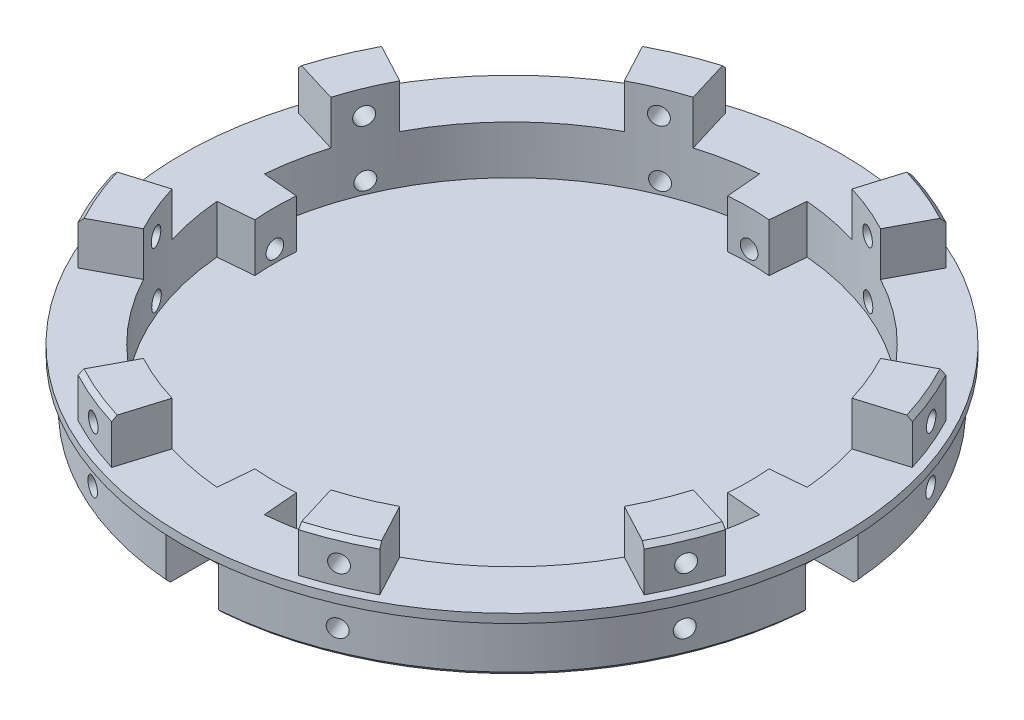
SolidWorks part; units mm, degrees
material "7075-T6, Piastra (SS)"
ref_plane "Piano frontale" through (0, 0, 0) normal (0, 0, 1) x (1, 0, 0)
ref_plane "Piano superiore" through (0, 0, 0) normal (0, 1, 0) x (1, 0, 0)
ref_plane "Piano destro" through (0, 0, 0) normal (1, 0, 0) x (0, 0, -1)
sketch "Schizzo1" plane through (0, 0, 0) normal (0, 0, 1) x (1, 0, 0)
  line L1 (-73, 24) -> (-62, 24)
  line L4 (0, 3) -> (0, 0)
  line L5 (0, 0) -> (-73, 0)
  line L7 (-73, 12) -> (-73, 0)
  line L10 (0, 0) -> (0, 105.2736) construction
  line L12 (-62, 3) -> (0, 3)
  line L13 (-73, 12) -> (-75, 12)
  line L14 (-75, 12) -> (-75, 14)
  line L15 (-75, 14) -> (-73, 14)
  line L16 (-73, 14) -> (-73, 24)
  line L19 (-62, 3) -> (-62, 0)
  line L20 (-62, 24) -> (-62, 3)
  dimension "D1" = 146
  dimension "D2" = 14
  dimension "D3" = 150
  dimension "D4" = 24
  dimension "D5" = 12
  dimension "D6" = 124
  dimension "D9" = 3
revolve "Rivoluzione1" add sketch "Schizzo1" angle 360 about L10
sketch "Schizzo2" plane through (0, 0, 0) normal (0, -1, 0) x (1, 0, 0)
  line L0 (0, 0) -> (-73, 0) construction
  line L1 (-72.753, 6) -> (-62.753, 6)
  line L2 (-62.753, 6) -> (-62.753, -6)
  line L3 (-62.753, -6) -> (-72.753, -6)
  circle A0 centre (0, 0) radius 73 construction
  arc A1 (-72.753, -6) -> (-72.753, 6) centre (0, 0) cw
  circle A2 centre (0, 0) radius 73 construction
  point P10 (-62.753, 0)
  dimension "D1" = 12
  dimension "D2" = 10
extrude "Taglio-Estrusione1" cut sketch "Schizzo2" against normal up to surface (12 mm away) up to face at (0, 12, -75)
sketch "Schizzo3" plane through (0, 24, 0) normal (0, 1, 0) x (1, 0, 0)
  line L0 (0, 0) -> (-73, 0) construction
  line L4 (0, 0) -> (-51.6188, 51.6188) construction
  line L7 (-43.8406, 43.8406) -> (-51.6188, 51.6188)
  line L8 (0, 0) -> (-67.4432, 27.9359) construction
  line L9 (0, 0) -> (-59.3078, 18.0717) construction
  line L10 (0, 0) -> (-54.7156, 29.1583) construction
  line L11 (-59.3078, 18.0717) -> (-69.8301, 21.278)
  line L12 (-54.7156, 29.1583) -> (-64.4232, 34.3315)
  line L13 (-59.3078, 18.0717) -> (-54.7156, 29.1583) construction
  line L14 (-62, 0) -> (-73, 0)
  circle A2 centre (0, 0) radius 62 construction
  arc A5 (-59.3078, 18.0717) -> (-43.8406, 43.8406) centre (0, 0) cw
  circle A6 centre (0, 0) radius 73 construction
  arc A7 (-69.8301, 21.278) -> (-51.6188, 51.6188) centre (0, 0) cw
  arc A8 (-69.8301, 21.278) -> (-64.4232, 34.3315) centre (0, 0) cw
  arc A9 (-62, 0) -> (-59.3078, 18.0717) centre (0, 0) cw
  arc A10 (-73, 0) -> (-69.8301, 21.278) centre (0, 0) cw
  point P19 (-57.0117, 23.615)
  dimension "D2" = 45
  dimension "D1" = 22.5
  dimension "D4" = 12
extrude "Taglio-Estrusione3" cut sketch "Schizzo3" against normal up to surface (10 mm away)
hole_wizard "Foro Ø4.0 (4)-1" positions "Schizzo3D1" profile "Schizzo5" hole size "Ø4.0" standard "ISO"
sketch3d "Schizzo3D1"
  point P0 (-67.4812, 18.5213, -27.8441)
sketch "Schizzo5" plane through (-67.4812, 18.5213, -27.8441) normal (0, 1, 0) x (-0.3814, 0, 0.9244)
  line L0 (0, 0) -> (0, 19)
  line L1 (0, 19) -> (2, 17.7983)
  line L2 (2, 17.7983) -> (2, 0)
  line L5 (2, 0) -> (0, 0)
  line L10 (0, 19) -> (-2, 17.7983) construction
  line L11 (0, -6.35) -> (0, 107.95) construction
  dimension "Hole Dia." = 4
  dimension "Hole Depth" = 19
  dimension "Drill Angle" = 118
hole_wizard "Foro Ø4.0 (4)-2" positions "Schizzo6" profile "Schizzo7" hole size "Ø4.0" standard "ISO"
sketch "Schizzo6" plane through (-62.753, 0, 0) normal (-1, 0, 0) x (0, 0, 1)
  point P0 (0, 5.7708)
sketch "Schizzo7" plane through (-62.753, 5.7708, 0) normal (0, 1, 0) x (0, 0, 1)
  line L0 (0, 0) -> (0, 19)
  line L1 (0, 19) -> (2, 17.7983)
  line L2 (2, 17.7983) -> (2, 0)
  line L5 (2, 0) -> (0, 0)
  line L10 (0, 19) -> (-2, 17.7983) construction
  line L11 (0, -6.35) -> (0, 107.95) construction
  dimension "Hole Dia." = 4
  dimension "Hole Depth" = 19
  dimension "Drill Angle" = 118
chamfer "Smusso1" distance 1 angle 45 1 edges at (73, 0, 0)
chamfer "Smusso2" distance 1 angle 45 1 edges at (-62.753, 0, 0)
fillet "Raccordo1" radius 1 1 edges at (-62.753, 12, 0)
chamfer "Smusso3" distance 1 angle 45 1 edges at (-67.4432, 24, -27.9359)
pattern_circular "RipetizioneCircolare5" count 8 over 360 about axis through (0, 0, 0) along (0, 1, 0) of "Foro Ø4.0 (4)-1", "Smusso3", "Taglio-Estrusione3"
pattern_circular "RipetizioneCircolare6" count 4 over 360 skipping 1, 2, 3 of "Taglio-Estrusione1", "Foro Ø4.0 (4)-2", "Raccordo1", "Smusso2"
hole_wizard "Foro Ø4.0 (4)-3" positions "Schizzo3D3" profile "Schizzo9" hole size "Ø4.0" standard "ISO"
sketch3d "Schizzo3D3"
  point P0 (-67.4973, 5.7088, 27.805)
  point P2 (-67.4973, 5.7088, 27.805)
sketch "Schizzo9" plane through (-67.4973, 5.7088, 27.805) normal (0, 1, 0) x (0.3809, 0, 0.9246)
  line L0 (0, 0) -> (0, 19)
  line L1 (0, 19) -> (2, 17.7983)
  line L2 (2, 17.7983) -> (2, 0)
  line L5 (2, 0) -> (0, 0)
  line L10 (0, 19) -> (-2, 17.7983) construction
  line L11 (0, -6.35) -> (0, 107.95) construction
  dimension "Hole Dia." = 4
  dimension "Hole Depth" = 19
  dimension "Drill Angle" = 118
pattern_circular "RipetizioneCircolare7" count 8 over 360 about axis through (0, 1, 0) along (0, -1, 0) of "Foro Ø4.0 (4)-3"
sketch "Schizzo10" [suppressed] plane through (0, 3, 0) normal (0, 1, 0) x (1, 0, 0)
  circle A0 centre (0, 0) radius 62
  arc A1 (-29.1583, 54.7156) -> (-54.7156, 29.1583) centre (0, 0) ccw construction
extrude "Taglio-Estrusione4" [suppressed] cut sketch "Schizzo10" against normal blind 10
sketch "Schizzo11" plane through (0, 3, 0) normal (0, 1, 0) x (1, 0, 0)
  line L0 (-4.7064, 53.7945) -> (-5.4037, 61.7641)
  line L1 (0, 54) -> (0, 0) construction
  line L2 (4.7064, 53.7945) -> (5.4037, 61.7641)
  line L3 (-4.7064, 53.7945) -> (0, 0) construction
  line L4 (0, 0) -> (4.7064, 53.7945) construction
  arc A0 (18.0717, 59.3078) -> (-18.0717, 59.3078) centre (0, 0) ccw construction
  arc A1 (-4.7064, 53.7945) -> (4.7064, 53.7945) centre (0, 0) cw
  arc A3 (-5.4037, 61.7641) -> (5.4037, 61.7641) centre (0, 0) cw
  point P6 (0, 0)
  point P10 (0, 0)
  point P12 (0, 0)
  point P13 (0, 0)
  point P14 (0, 0)
  circle M4 centre (0, 0) radius 62
  dimension "D1" = 54
  dimension "D2" = 10
extrude "Estrusione-Estrusione1" add sketch "Schizzo11" along a picked direction on the side of the normal blind 11 contours L0 A1 L2 M4
pattern_circular "RipetizioneCircolare8" count 4 over 360 about axis through (0, 0, 0) along (0, -1, 0) of "Estrusione-Estrusione1"
sketch "Schizzo12" plane through (-62.753, 0, 0) normal (-1, 0, 0) x (0, 0, 1)
  circle A0 centre (0, 5.7708) radius 2
  circle A1 centre (0, 5.7708) radius 2 construction
extrude "Taglio-Estrusione5" cut sketch "Schizzo12" against normal blind 10
pattern_circular "RipetizioneCircolare9" count 4 over 360 about axis through (0, 0, 0) along (0, 1, 0) of "Taglio-Estrusione1", "Foro Ø4.0 (4)-2"
